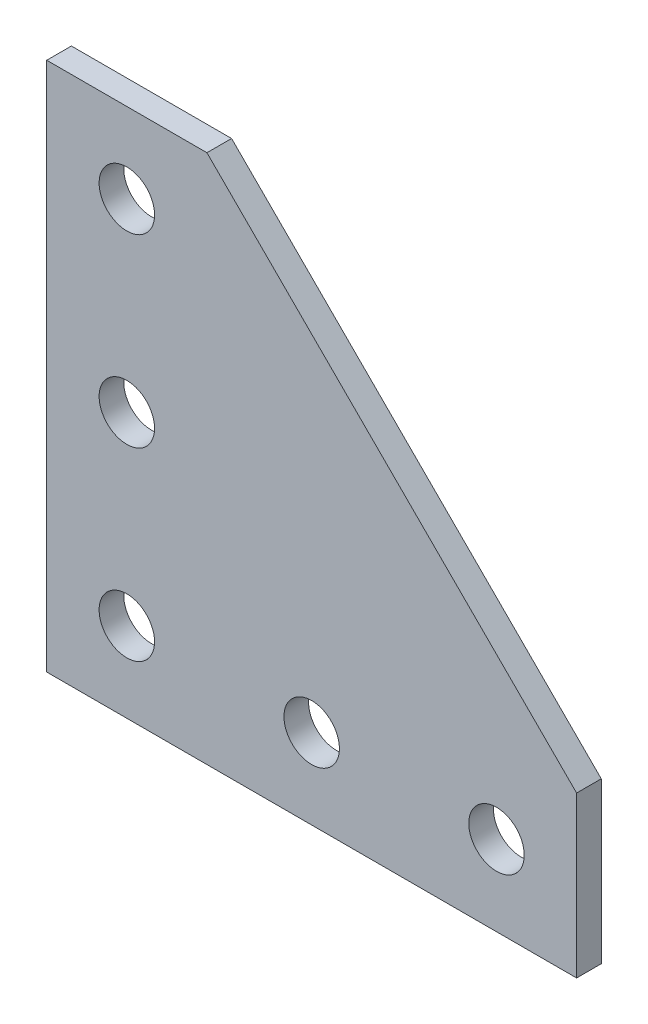
SolidWorks part; units mm, degrees
ref_plane "Front Plane" through (0, 0, 0) normal (0, 0, 1) x (1, 0, 0)
ref_plane "Top Plane" through (0, 0, 0) normal (0, 1, 0) x (1, 0, 0)
ref_plane "Right Plane" through (0, 0, 0) normal (1, 0, 0) x (0, 0, -1)
sketch "Sketch1" plane through (0, 0, 0) normal (0, 0, 1) x (1, 0, 0)
  line L0 (-88.9, 47.625) -> (-47.625, 47.625)
  line L1 (-47.625, 47.625) -> (47.625, -47.625)
  line L2 (47.625, -47.625) -> (47.625, -88.9)
  line L3 (47.625, -88.9) -> (-88.9, -88.9)
  line L4 (-88.9, -88.9) -> (-88.9, 47.625)
  line L5 (-68.2625, 47.625) -> (-68.2625, -68.2625) construction
  line L6 (-68.2625, -68.2625) -> (47.625, -68.2625) construction
  circle A0 centre (-68.2625, -68.2625) radius 7.1437
  circle A1 centre (-68.2625, -20.6375) radius 7.1437
  circle A2 centre (-68.2625, 26.9875) radius 7.1437
  circle A3 centre (-20.6375, -68.2625) radius 7.1438
  circle A4 centre (26.9875, -68.2625) radius 7.1437
  dimension "Hole Size" = 14.2875
  dimension "D1" = 45
  dimension "A" = 136.525
  dimension "D3" = 41.275
  dimension "D5" = 47.625
  dimension "D6" = 47.625
  dimension "D7" = 47.625
  dimension "Spacing" = 47.625
extrude "Boss-Extrude1" add sketch "Sketch1" along normal mid plane 6.35
sketch "Sketch2" plane through (0, 0, 3.175) normal (0, 0, 1) x (1, 0, 0)
  circle A0 centre (-68.2625, 26.9875) radius 7.1437 construction
  circle A1 centre (-68.2625, 26.9875) radius 7.1437
  circle A2 centre (26.9875, -68.2625) radius 7.1437 construction
  circle A3 centre (-20.6375, -68.2625) radius 7.1438 construction
  circle A4 centre (-68.2625, -68.2625) radius 7.1437 construction
  circle A5 centre (-68.2625, -20.6375) radius 7.1437 construction
  circle A6 centre (26.9875, -68.2625) radius 7.1437
  circle A7 centre (-20.6375, -68.2625) radius 7.1438
  circle A8 centre (-68.2625, -68.2625) radius 7.1437
  circle A9 centre (-68.2625, -20.6375) radius 7.1437
extrude "Boss-Extrude2" [suppressed] add sketch "Sketch2" against normal through all
equation "\"D7@Sketch1\" = \"Spacing@Sketch1\""
equation "\"D5@Sketch1\" = \"Spacing@Sketch1\""
equation "\"D6@Sketch1\" = \"Spacing@Sketch1\""
